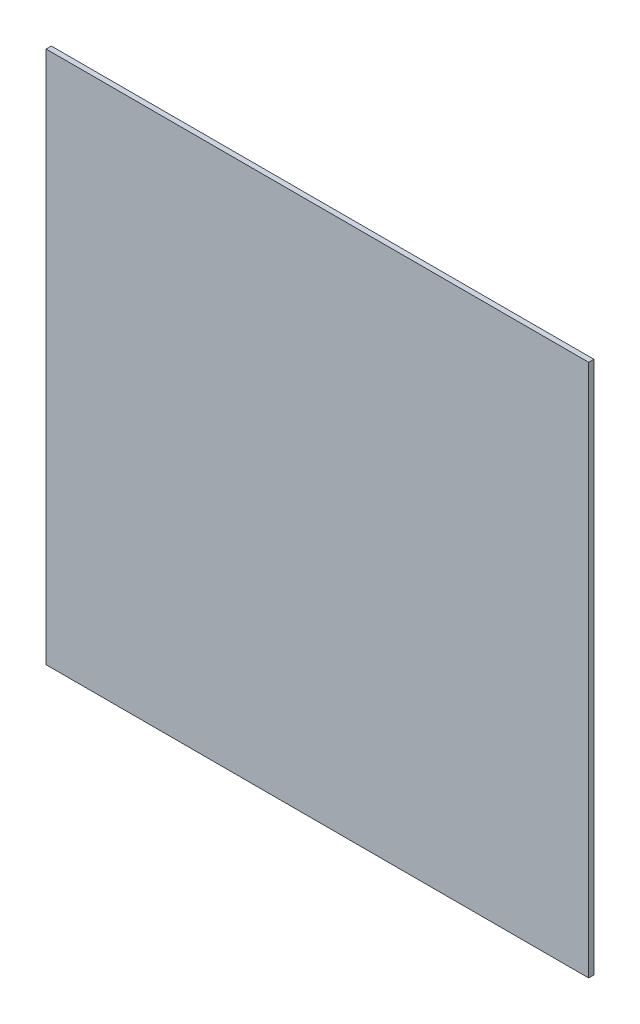
SolidWorks part; units mm, degrees
ref_plane "前视基准面" through (0, 0, 0) normal (0, 0, 1) x (1, 0, 0)
ref_plane "上视基准面" through (0, 0, 0) normal (0, 1, 0) x (1, 0, 0)
ref_plane "右视基准面" through (0, 0, 0) normal (1, 0, 0) x (0, 0, -1)
sketch "草图1" plane through (0, 0, 0) normal (0, 0, 1) x (1, 0, 0)
  line L1 (-41.028, 64.7789) -> (62.772, 64.7789)
  line L2 (-41.028, 64.7789) -> (-41.028, -37.2211)
  line L3 (-41.028, -37.2211) -> (62.772, -37.2211)
  line L4 (62.772, 64.7789) -> (62.772, -37.2211)
extrude "凸台-拉伸1" add sketch "草图1" along normal blind 1
sketch "草图2" plane through (0, 0, 1) normal (0, 0, 1) x (1, 0, 0)
  line L0 (-41.028, -37.2211) -> (62.772, -37.2211) construction
  line L1 (-34.028, 61.2789) -> (52.772, 61.2789)
  line L2 (-34.028, 61.2789) -> (-34.028, -33.7211)
  line L3 (-34.028, -33.7211) -> (52.772, -33.7211)
  line L4 (52.772, 61.2789) -> (52.772, -33.7211)
  line L5 (-41.028, 64.7789) -> (-41.028, -37.2211) construction
  line L8 (62.772, -37.2211) -> (62.772, 64.7789) construction
  dimension "D1" = 95
  dimension "D2" = 3.5
  dimension "D3" = 7
  dimension "D4" = 10
sketch "草图3" plane through (0, 0, 1) normal (0, 0, 1) x (1, 0, 0)
  line L0 (-41.028, 64.7789) -> (-41.028, -37.2211) construction
  line L1 (-31.028, 57.7789) -> (52.772, 57.7789)
  line L2 (-31.028, 57.7789) -> (-31.028, -30.2211)
  line L3 (-31.028, -30.2211) -> (52.772, -30.2211)
  line L4 (52.772, 57.7789) -> (52.772, -30.2211)
  line L5 (62.772, -37.2211) -> (62.772, 64.7789) construction
  line L9 (-41.028, -37.2211) -> (62.772, -37.2211) construction
  line L10 (62.772, 64.7789) -> (-41.028, 64.7789) construction
  dimension "D1" = 10
  dimension "D2" = 10
  dimension "D3" = 7
  dimension "D4" = 7
